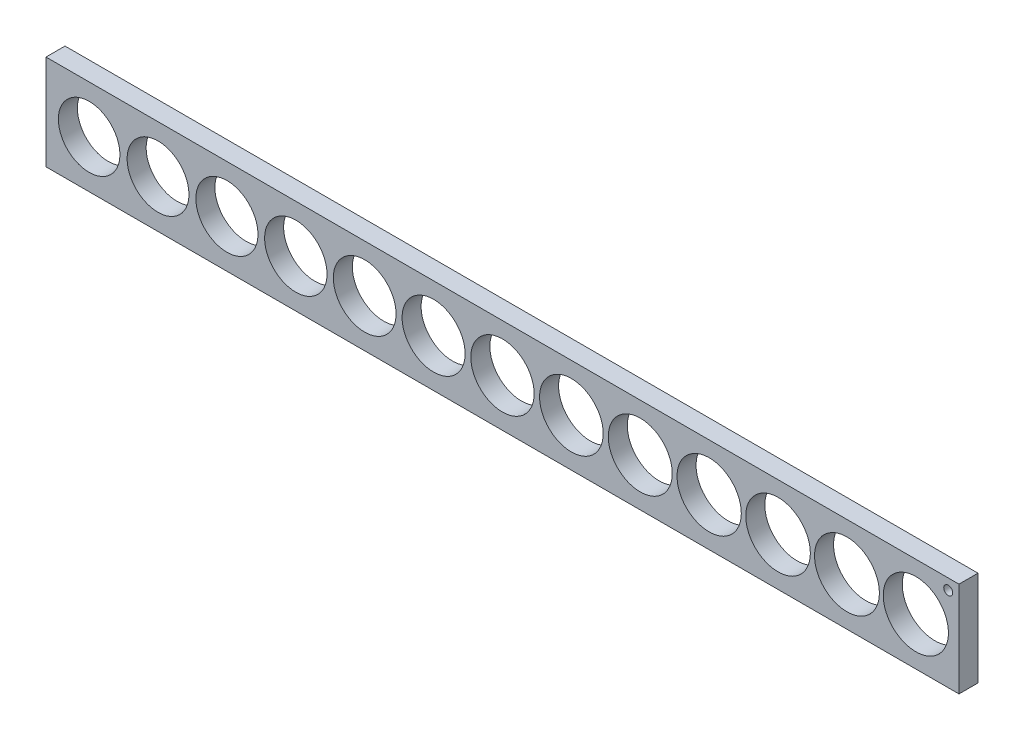
SolidWorks part; units mm, degrees
material "Custom Plastic"
ref_plane "X-Y Datum" through (0, 0, 0) normal (0, 0, 1) x (1, 0, 0)
ref_plane "X-Z Datum" through (0, 0, 0) normal (0, 1, 0) x (1, 0, 0)
ref_plane "Y-Z Datum" through (0, 0, 0) normal (1, 0, 0) x (0, 0, -1)
sketch "Sketch1" plane through (0, 0, 0) normal (0, 0, 1) x (1, 0, 0)
  line L0 (-152.4, 0) -> (152.4, 0) construction
  line L1 (-152.4, 15.875) -> (152.4, 15.875)
  line L2 (-152.4, 15.875) -> (-152.4, -15.875)
  line L3 (-152.4, -15.875) -> (152.4, -15.875)
  line L4 (152.4, 15.875) -> (152.4, -15.875)
  line L5 (-152.4, 15.875) -> (152.4, -15.875) construction
  line L6 (-152.4, -15.875) -> (152.4, 15.875) construction
  line L7 (0, -55) -> (0, 55) construction
  line L8 (148.8079, 12.2829) -> (152.4, 15.875) construction
  circle A0 centre (0, 0) radius 10.575
  circle A1 centre (23, 0) radius 10.575 construction
  circle A2 centre (46, 0) radius 10.575 construction
  circle A3 centre (69, 0) radius 10.575 construction
  circle A4 centre (92, 0) radius 10.575 construction
  circle A5 centre (115, 0) radius 10.575 construction
  circle A7 centre (-115, 0) radius 10.575 construction
  circle A8 centre (-92, 0) radius 10.575 construction
  circle A9 centre (-69, 0) radius 10.575 construction
  circle A10 centre (-46, 0) radius 10.575 construction
  circle A11 centre (-23, 0) radius 10.575 construction
  circle A12 centre (23, 0) radius 10.6258
  circle A13 centre (46, 0) radius 10.6766
  circle A14 centre (69, 0) radius 10.7274
  circle A15 centre (92, 0) radius 10.7782
  circle A16 centre (115, 0) radius 10.829
  circle A17 centre (138, 0) radius 10.575 construction
  circle A18 centre (-138, 0) radius 10.575 construction
  circle A19 centre (138, 0) radius 10.8798
  circle A20 centre (-138, 0) radius 10.2702
  circle A21 centre (-115, 0) radius 10.321
  circle A22 centre (-92, 0) radius 10.3718
  circle A23 centre (-69, 0) radius 10.4226
  circle A24 centre (-46, 0) radius 10.4734
  circle A25 centre (-23, 0) radius 10.5242
  circle A26 centre (148.8079, 12.2829) radius 1.5
  point P0 (0, 0)
  dimension "D1" = 21.15
  dimension "D22" = 3
  dimension "D23" = 20.5404
  dimension "D24" = 20.642
  dimension "D25" = 20.7436
  dimension "D26" = 20.8452
  dimension "D27" = 20.9468
  dimension "D28" = 21.0484
  dimension "D29" = 21.2516
  dimension "D30" = 21.3532
  dimension "D31" = 21.4548
  dimension "D32" = 21.5564
  dimension "D33" = 21.658
  dimension "D34" = 21.7596
  dimension "D2" = 304.8
  dimension "D3" = 31.75
  dimension "D4" = 23
  dimension "D5" = 23
  dimension "D6" = 23
  dimension "D7" = 23
  dimension "D8" = 23
  dimension "D14" = 23
  dimension "D35" = 45
  dimension "D36" = 5.08
  dimension "D9" = 0.0508
  dimension "D10" = 0.1016
  dimension "D11" = 0.1524
  dimension "D12" = 0.2032
  dimension "D13" = 0.254
  dimension "D15" = 0.3048
  dimension "D16" = 0.3048
  dimension "D17" = 0.254
  dimension "D18" = 0.2032
  dimension "D19" = 0.1524
  dimension "D20" = 0.1016
  dimension "D21" = 0.0508
extrude "Boss-Extrude1" add sketch "Sketch1" along normal blind 6.35
